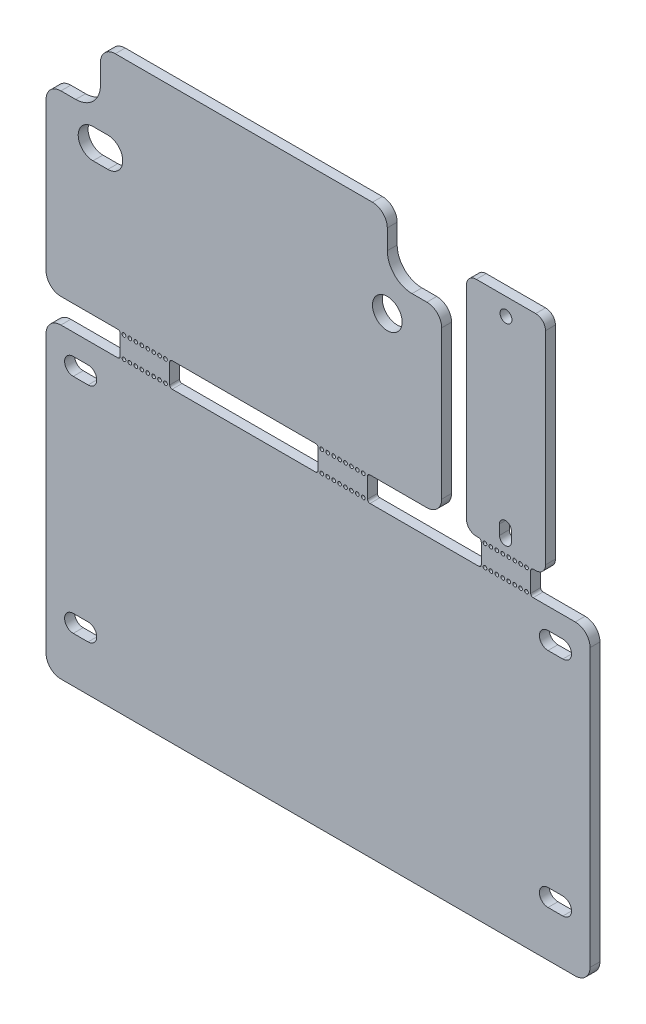
SolidWorks part; units mm, degrees
ref_plane "正面" through (0, 0, 0) normal (0, 0, 1) x (1, 0, 0)
ref_plane "平面" through (0, 0, 0) normal (0, 1, 0) x (1, 0, 0)
ref_plane "右側面" through (0, 0, 0) normal (1, 0, 0) x (0, 0, -1)
sketch "ｽｹｯﾁ1" plane through (0, 0, 0) normal (0, 0, 1) x (1, 0, 0)
  line L0 (-49.5, 24.75) -> (-46.5, 24.75)
  line L1 (55, 32.5) -> (-55, 32.5)
  line L2 (55, 32.5) -> (55, -32.5)
  line L3 (55, -32.5) -> (-55, -32.5)
  line L4 (-55, 32.5) -> (-55, -32.5)
  line L5 (55, 32.5) -> (-55, -32.5) construction
  line L6 (55, -32.5) -> (-55, 32.5) construction
  line L7 (-46.5, 28.25) -> (-49.5, 28.25)
  line L8 (-46.5, 28.25) -> (-46.5, 24.75) construction
  line L10 (-49.5, 28.25) -> (-49.5, 24.75) construction
  line L11 (-46.5, 28.25) -> (-49.5, 24.75) construction
  line L12 (-46.5, 24.75) -> (-49.5, 28.25) construction
  line L13 (-55, 4) -> (55, 4) construction
  line L14 (0, 32.5) -> (0, -32.5) construction
  line L15 (-46.5, -20.25) -> (-49.5, -20.25)
  line L16 (-49.5, -16.75) -> (-46.5, -16.75)
  line L17 (46.5, -20.25) -> (49.5, -20.25)
  line L18 (49.5, -16.75) -> (46.5, -16.75)
  line L19 (46.5, 28.25) -> (49.5, 28.25)
  line L20 (49.5, 24.75) -> (46.5, 24.75)
  arc A2 (-49.5, 28.25) -> (-49.5, 24.75) centre (-49.5, 26.5) ccw
  arc A3 (-46.5, 28.25) -> (-46.5, 24.75) centre (-46.5, 26.5) cw
  arc A4 (-49.5, -20.25) -> (-49.5, -16.75) centre (-49.5, -18.5) cw
  arc A5 (-46.5, -20.25) -> (-46.5, -16.75) centre (-46.5, -18.5) ccw
  arc A6 (46.5, -20.25) -> (46.5, -16.75) centre (46.5, -18.5) cw
  arc A7 (49.5, -20.25) -> (49.5, -16.75) centre (49.5, -18.5) ccw
  arc A8 (49.5, 28.25) -> (49.5, 24.75) centre (49.5, 26.5) cw
  arc A9 (46.5, 28.25) -> (46.5, 24.75) centre (46.5, 26.5) ccw
  point P0 (0, 0)
  point P6 (-48, 26.5)
  dimension "D3" = 3.5
  dimension "D4" = 3
  dimension "D1" = 65
  dimension "D2" = 110
  dimension "D5" = 6
  dimension "D6" = 7
  dimension "D7" = 22.5
extrude "ﾎﾞｽ - 押し出し1" add sketch "ｽｹｯﾁ1" along normal blind 2
fillet "ﾌｨﾚｯﾄ1" radius 3 2 edges at (55, 32.5, 1) (-55, 32.5, 1)
sketch "ｽｹｯﾁ2" plane through (0, 0, 2) normal (0, 0, 1) x (1, 0, 0)
  line L0 (-45.5, 64.5) -> (-42.5, 64.5)
  line L2 (-55, 85.5) -> (-55, 37.5) construction
  line L3 (-55, 37.5) -> (25, 37.5) construction
  line L4 (25, 85.5) -> (25, 37.5) construction
  line L5 (-55, 85.5) -> (25, 37.5) construction
  line L6 (-55, 37.5) -> (25, 85.5) construction
  line L7 (-45.5, 70.5) -> (-42.5, 70.5)
  line L8 (-45.5, 70.5) -> (-45.5, 64.5) construction
  line L10 (-42.5, 70.5) -> (-42.5, 64.5) construction
  line L11 (-45.5, 70.5) -> (-42.5, 64.5) construction
  line L12 (-45.5, 64.5) -> (-42.5, 70.5) construction
  line L17 (-44, 67.5) -> (14, 67.5) construction
  line L18 (-15, 85.5) -> (-15, 37.5) construction
  line L24 (-55, 85.5) -> (25, 85.5) construction
  line L25 (-55, 37.5) -> (25, 37.5)
  line L26 (25, 37.5) -> (25, 73.5)
  line L27 (25, 73.5) -> (14, 73.5)
  line L28 (14, 73.5) -> (14, 85.5)
  line L29 (14, 85.5) -> (-44, 85.5)
  line L30 (-44, 73.5) -> (-44, 85.5)
  line L31 (-55, 73.5) -> (-44, 73.5)
  line L32 (-55, 37.5) -> (-55, 73.5)
  line L33 (-55, 29.5) -> (-55, -32.5) construction
  line L34 (52, 32.5) -> (-52, 32.5) construction
  arc A0 (-45.5, 70.5) -> (-45.5, 64.5) centre (-45.5, 67.5) ccw
  arc A1 (-42.5, 70.5) -> (-42.5, 64.5) centre (-42.5, 67.5) cw
  circle A2 centre (14, 67.5) radius 3
  point P0 (-15, 61.5)
  point P5 (-44, 67.5)
  dimension "D6" = 6
  dimension "D7" = 29
  dimension "D1" = 80
  dimension "D2" = 48
  dimension "D3" = 6
  dimension "D4" = 3
  dimension "D5" = 29
  dimension "D8" = 12
  dimension "D9" = 11
  dimension "D10" = 18
  dimension "D11" = 5
extrude "ﾎﾞｽ - 押し出し2" add sketch "ｽｹｯﾁ2" against normal blind 2 separate body
fillet "ﾌｨﾚｯﾄ5" radius 3 6 edges at (-44, 85.5, 1) (-55, 73.5, 1) (14, 85.5, 1) (25, 73.5, 1) (25, 37.5, 1) (-55, 37.5, 1)
fillet "ﾌｨﾚｯﾄ6" radius 5 2 edges at (14, 73.5, 1) (-44, 73.5, 1)
sketch "ｽｹｯﾁ4" plane through (0, 0, 2) normal (0, 0, 1) x (1, 0, 0)
  line L0 (-40, 37.5) -> (-40, 32.5)
  line L1 (-52, 37.5) -> (22, 37.5) construction
  line L2 (52, 32.5) -> (-52, 32.5) construction
  line L3 (-40, 32.5) -> (-30, 32.5)
  line L4 (-30, 32.5) -> (-30, 37.5)
  line L5 (-30, 37.5) -> (-40, 37.5)
  line L6 (0, 37.5) -> (0, 32.5)
  line L7 (0, 32.5) -> (10, 32.5)
  line L8 (10, 32.5) -> (10, 37.5)
  line L9 (10, 37.5) -> (0, 37.5)
  line L10 (-55, 70.5) -> (-55, 40.5) construction
  line L11 (25, 40.5) -> (25, 70.5) construction
  dimension "D1" = 10
  dimension "D2" = 10
  dimension "D3" = 15
  dimension "D4" = 15
extrude "ﾎﾞｽ - 押し出し4" add sketch "ｽｹｯﾁ4" against normal blind 2
fillet "ﾌｨﾚｯﾄ7" radius 0.5 8 edges at (10, 37.5, 1) (10, 32.5, 1) (0, 37.5, 1) (0, 32.5, 1) (-30, 37.5, 1) (-30, 32.5, 1) (-40, 37.5, 1) (-40, 32.5, 1)
sketch "ｽｹｯﾁ5" plane through (0, 0, 2) normal (0, 0, 1) x (1, 0, 0)
  line L0 (36.6832, 42) -> (36.6832, 40)
  line L1 (30, 82.5) -> (46, 82.5)
  line L2 (30, 82.5) -> (30, 37.5)
  line L3 (30, 37.5) -> (46, 37.5)
  line L4 (46, 82.5) -> (46, 37.5)
  line L5 (30, 82.5) -> (46, 37.5) construction
  line L6 (30, 37.5) -> (46, 82.5) construction
  line L7 (39.0832, 42) -> (36.6832, 42) construction
  line L8 (39.0832, 42) -> (39.0832, 40)
  line L9 (39.0832, 40) -> (36.6832, 40) construction
  line L11 (39.0832, 42) -> (36.6832, 40) construction
  line L12 (39.0832, 40) -> (36.6832, 42) construction
  line L13 (25, 40.5) -> (25, 70.5) construction
  line L14 (52, 32.5) -> (10.5, 32.5) construction
  circle A0 centre (38, 79) radius 1.2
  arc A1 (36.6832, 42) -> (39.0832, 42) centre (37.8832, 42) cw
  arc A2 (39.0832, 40) -> (36.6832, 40) centre (37.8832, 40) cw
  point P0 (38, 60)
  point P7 (37.8832, 41)
  dimension "D3" = 2.4
  dimension "D1" = 45
  dimension "D2" = 16
  dimension "D4" = 2.4
  dimension "D5" = 2
  dimension "D6" = 19
  dimension "D7" = 19
  dimension "D8" = 5
  dimension "D9" = 5
extrude "ﾎﾞｽ - 押し出し5" add sketch "ｽｹｯﾁ5" against normal blind 2 separate body
sketch "ｽｹｯﾁ6" plane through (0, 0, 2) normal (0, 0, 1) x (1, 0, 0)
  line L0 (33, 37.5) -> (33, 32.5)
  line L1 (30, 37.5) -> (46, 37.5) construction
  line L2 (52, 32.5) -> (10.5, 32.5) construction
  line L3 (33, 32.5) -> (43, 32.5)
  line L4 (43, 32.5) -> (43, 37.5)
  line L5 (43, 37.5) -> (33, 37.5)
  line L6 (25, 65.5) -> (30, 65.5)
  line L7 (25, 40.5) -> (25, 70.5) construction
  line L8 (30, 82.5) -> (30, 37.5) construction
  line L9 (30, 65.5) -> (30, 55.5)
  line L10 (30, 55.5) -> (25, 55.5)
  line L11 (25, 55.5) -> (25, 65.5)
  line L13 (10.5, 37.5) -> (22, 37.5) construction
  dimension "D1" = 10
  dimension "D2" = 10
  dimension "D3" = 3
  dimension "D4" = 18
extrude "ﾎﾞｽ - 押し出し6" add sketch "ｽｹｯﾁ6" against normal blind 2
fillet "ﾌｨﾚｯﾄ8" radius 0.5 8 edges at (43, 32.5, 1) (43, 37.5, 1) (33, 32.5, 1) (33, 37.5, 1) (30, 55.5, 1) (25, 55.5, 1) (25, 65.5, 1) (30, 65.5, 1)
fillet "ﾌｨﾚｯﾄ9" radius 2 4 edges at (46, 82.5, 1) (30, 82.5, 1) (46, 37.5, 1) (30, 37.5, 1)
sketch "ｽｹｯﾁ7" plane through (0, 0, 2) normal (0, 0, 1) x (1, 0, 0)
  line L0 (-55, -32.5) -> (55, -32.5)
  line L1 (55, -32.5) -> (55, -29.5)
  line L2 (55, -32.5) -> (55, 29.5) construction
  line L3 (55, -29.5) -> (-55, -29.5)
  line L4 (-55, 29.5) -> (-55, -32.5) construction
  line L5 (-55, -29.5) -> (-55, -32.5)
  dimension "D1" = 3
extrude "ｶｯﾄ - 押し出し1" cut sketch "ｽｹｯﾁ7" against normal blind 10
fillet "ﾌｨﾚｯﾄ10" radius 3 2 edges at (55, -29.5, 1) (-55, -29.5, 1)
sketch "ｽｹｯﾁ8" plane through (0, 0, 2) normal (0, 0, 1) x (1, 0, 0)
  line L0 (-40.5, 37.5) -> (-29.5, 37.5) construction
  line L1 (-40, 37.25) -> (-30, 37.25) construction
  line L2 (-40, 37) -> (-40, 33) construction
  line L3 (-30, 33) -> (-30, 37) construction
  line L4 (-40, 35) -> (-30, 35) construction
  line L5 (-15, 37.5) -> (-15, 32.5) construction
  line L6 (-29.5, 37.5) -> (-0.5, 37.5) construction
  line L7 (-0.5, 32.5) -> (-29.5, 32.5) construction
  line L8 (21.5, 32.5) -> (21.5, 37.5) construction
  line L9 (32.5, 32.5) -> (10.5, 32.5) construction
  line L10 (10.5, 37.5) -> (22, 37.5) construction
  circle A0 centre (-39.5, 37.25) radius 0.25
  circle A1 centre (-38.75, 37.25) radius 0.25
  circle A2 centre (-38, 37.25) radius 0.25
  circle A3 centre (-37.25, 37.25) radius 0.25
  circle A4 centre (-36.5, 37.25) radius 0.25
  circle A5 centre (-35.75, 37.25) radius 0.25
  circle A6 centre (-35, 37.25) radius 0.25
  circle A7 centre (-34.25, 37.25) radius 0.25
  circle A8 centre (-33.5, 37.25) radius 0.25
  circle A9 centre (-32.75, 37.25) radius 0.25
  circle A10 centre (-32, 37.25) radius 0.25
  circle A11 centre (-31.25, 37.25) radius 0.25
  circle A12 centre (-30.5, 37.25) radius 0.25
  circle A13 centre (-30.5, 32.75) radius 0.25
  circle A14 centre (-31.25, 32.75) radius 0.25
  circle A15 centre (-32, 32.75) radius 0.25
  circle A16 centre (-32.75, 32.75) radius 0.25
  circle A17 centre (-33.5, 32.75) radius 0.25
  circle A18 centre (-34.25, 32.75) radius 0.25
  circle A19 centre (-35, 32.75) radius 0.25
  circle A20 centre (-35.75, 32.75) radius 0.25
  circle A21 centre (-36.5, 32.75) radius 0.25
  circle A22 centre (-37.25, 32.75) radius 0.25
  circle A23 centre (-38, 32.75) radius 0.25
  circle A24 centre (-38.75, 32.75) radius 0.25
  circle A25 centre (-39.5, 32.75) radius 0.25
  circle A26 centre (0.5, 32.75) radius 0.25
  circle A27 centre (1.25, 32.75) radius 0.25
  circle A28 centre (2, 32.75) radius 0.25
  circle A29 centre (2.75, 32.75) radius 0.25
  circle A30 centre (3.5, 32.75) radius 0.25
  circle A31 centre (4.25, 32.75) radius 0.25
  circle A32 centre (5, 32.75) radius 0.25
  circle A33 centre (5.75, 32.75) radius 0.25
  circle A34 centre (6.5, 32.75) radius 0.25
  circle A35 centre (7.25, 32.75) radius 0.25
  circle A36 centre (8, 32.75) radius 0.25
  circle A37 centre (8.75, 32.75) radius 0.25
  circle A38 centre (9.5, 32.75) radius 0.25
  circle A39 centre (0.5, 37.25) radius 0.25
  circle A40 centre (1.25, 37.25) radius 0.25
  circle A41 centre (2, 37.25) radius 0.25
  circle A42 centre (2.75, 37.25) radius 0.25
  circle A43 centre (3.5, 37.25) radius 0.25
  circle A44 centre (4.25, 37.25) radius 0.25
  circle A45 centre (5, 37.25) radius 0.25
  circle A46 centre (5.75, 37.25) radius 0.25
  circle A47 centre (6.5, 37.25) radius 0.25
  circle A48 centre (7.25, 37.25) radius 0.25
  circle A49 centre (8, 37.25) radius 0.25
  circle A50 centre (8.75, 37.25) radius 0.25
  circle A51 centre (9.5, 37.25) radius 0.25
  circle A52 centre (33.5, 32.75) radius 0.25
  circle A53 centre (34.25, 32.75) radius 0.25
  circle A54 centre (35, 32.75) radius 0.25
  circle A55 centre (35.75, 32.75) radius 0.25
  circle A56 centre (36.5, 32.75) radius 0.25
  circle A57 centre (37.25, 32.75) radius 0.25
  circle A58 centre (38, 32.75) radius 0.25
  circle A59 centre (38.75, 32.75) radius 0.25
  circle A60 centre (39.5, 32.75) radius 0.25
  circle A61 centre (40.25, 32.75) radius 0.25
  circle A62 centre (41, 32.75) radius 0.25
  circle A63 centre (41.75, 32.75) radius 0.25
  circle A64 centre (42.5, 32.75) radius 0.25
  circle A65 centre (33.5, 37.25) radius 0.25
  circle A66 centre (34.25, 37.25) radius 0.25
  circle A67 centre (35, 37.25) radius 0.25
  circle A68 centre (35.75, 37.25) radius 0.25
  circle A69 centre (36.5, 37.25) radius 0.25
  circle A70 centre (37.25, 37.25) radius 0.25
  circle A71 centre (38, 37.25) radius 0.25
  circle A72 centre (38.75, 37.25) radius 0.25
  circle A73 centre (39.5, 37.25) radius 0.25
  circle A74 centre (40.25, 37.25) radius 0.25
  circle A75 centre (41, 37.25) radius 0.25
  circle A76 centre (41.75, 37.25) radius 0.25
  circle A77 centre (42.5, 37.25) radius 0.25
  dimension "D2" = 0.5
  dimension "D3" = 0.5
  dimension "D1" = 0.25
  dimension "D4" = 13
sketch "ｽｹｯﾁ10" plane through (0, 0, 2) normal (0, 0, 1) x (1, 0, 0)
  line L1 (30, 70.4209) -> (25, 70.4209)
  line L2 (30, 70.4209) -> (30, 50.5791)
  line L3 (30, 50.5791) -> (25, 50.5791)
  line L4 (25, 70.4209) -> (25, 50.5791)
  line L5 (30, 70.4209) -> (25, 50.5791) construction
  line L6 (30, 50.5791) -> (25, 70.4209) construction
  line L7 (25, 40.5) -> (25, 55) construction
  point P0 (27.5, 60.5)
  dimension "D1" = 5
extrude "ｶｯﾄ - 押し出し3" cut sketch "ｽｹｯﾁ10" against normal blind 10
sketch "ｽｹｯﾁ11" plane through (0, 0, 2) normal (0, 0, 1) x (1, 0, 0)
  line L0 (-40.0159, 37.125) -> (-29.9841, 37.125) construction
  line L2 (-40, 37) -> (-40, 33) construction
  line L3 (-52, 37.5) -> (-40.5, 37.5) construction
  line L4 (-0.0159, 37.125) -> (10.0159, 37.125) construction
  line L5 (-29.5, 37.5) -> (-0.5, 37.5) construction
  line L6 (0, 37) -> (0, 33) construction
  line L7 (32.9841, 37.125) -> (43.0159, 37.125) construction
  line L8 (33, 37) -> (33, 33) construction
  line L9 (-40, 35) -> (43, 35) construction
  line L10 (43, 33) -> (43, 37) construction
  circle A0 centre (-39.25, 37.125) radius 0.375
  arc A1 (-40, 37) -> (-40.5, 37.5) centre (-40.5, 37) ccw construction
  arc A2 (-29.5, 37.5) -> (-30, 37) centre (-29.5, 37) ccw construction
  circle A3 centre (-38.05, 37.125) radius 0.375
  circle A4 centre (-36.85, 37.125) radius 0.375
  circle A5 centre (-35.65, 37.125) radius 0.375
  circle A6 centre (-34.45, 37.125) radius 0.375
  circle A7 centre (-33.25, 37.125) radius 0.375
  circle A8 centre (-32.05, 37.125) radius 0.375
  circle A9 centre (-30.85, 37.125) radius 0.375
  arc A10 (0, 37) -> (-0.5, 37.5) centre (-0.5, 37) ccw construction
  arc A11 (10.5, 37.5) -> (10, 37) centre (10.5, 37) ccw construction
  circle A12 centre (0.75, 37.125) radius 0.375
  arc A13 (33, 37) -> (32.5, 37.5) centre (32.5, 37) ccw construction
  arc A14 (43.5, 37.5) -> (43, 37) centre (43.5, 37) ccw construction
  circle A15 centre (33.75, 37.125) radius 0.375
  circle A16 centre (34.95, 37.125) radius 0.375
  circle A17 centre (36.15, 37.125) radius 0.375
  circle A18 centre (37.35, 37.125) radius 0.375
  circle A19 centre (38.55, 37.125) radius 0.375
  circle A20 centre (39.75, 37.125) radius 0.375
  circle A21 centre (40.95, 37.125) radius 0.375
  circle A22 centre (42.15, 37.125) radius 0.375
  circle A23 centre (1.95, 37.125) radius 0.375
  circle A24 centre (3.15, 37.125) radius 0.375
  circle A25 centre (4.35, 37.125) radius 0.375
  circle A26 centre (5.55, 37.125) radius 0.375
  circle A27 centre (6.75, 37.125) radius 0.375
  circle A28 centre (7.95, 37.125) radius 0.375
  circle A29 centre (9.15, 37.125) radius 0.375
  circle A30 centre (42.15, 32.875) radius 0.375
  circle A31 centre (40.95, 32.875) radius 0.375
  circle A32 centre (39.75, 32.875) radius 0.375
  circle A33 centre (38.55, 32.875) radius 0.375
  circle A34 centre (37.35, 32.875) radius 0.375
  circle A35 centre (36.15, 32.875) radius 0.375
  circle A36 centre (34.95, 32.875) radius 0.375
  circle A37 centre (33.75, 32.875) radius 0.375
  circle A38 centre (0.75, 32.875) radius 0.375
  circle A39 centre (1.95, 32.875) radius 0.375
  circle A40 centre (3.15, 32.875) radius 0.375
  circle A41 centre (4.35, 32.875) radius 0.375
  circle A42 centre (5.55, 32.875) radius 0.375
  circle A43 centre (6.75, 32.875) radius 0.375
  circle A44 centre (7.95, 32.875) radius 0.375
  circle A45 centre (9.15, 32.875) radius 0.375
  circle A46 centre (-30.85, 32.875) radius 0.375
  circle A47 centre (-32.05, 32.875) radius 0.375
  circle A48 centre (-33.25, 32.875) radius 0.375
  circle A49 centre (-34.45, 32.875) radius 0.375
  circle A50 centre (-35.65, 32.875) radius 0.375
  circle A51 centre (-36.85, 32.875) radius 0.375
  circle A52 centre (-38.05, 32.875) radius 0.375
  circle A53 centre (-39.25, 32.875) radius 0.375
  dimension "D1" = 0.75
  dimension "D2" = 0.75
  dimension "D6" = 0.75
  dimension "D7" = 0.75
  dimension "D8" = 0.75
  dimension "D3" = 0.375
  dimension "D5" = 0.375
  dimension "D9" = 0.75
  dimension "D4" = 8
  dimension "D10" = 8
  dimension "D11" = 8
extrude "ｶｯﾄ - 押し出し4" cut sketch "ｽｹｯﾁ11" against normal blind 10
